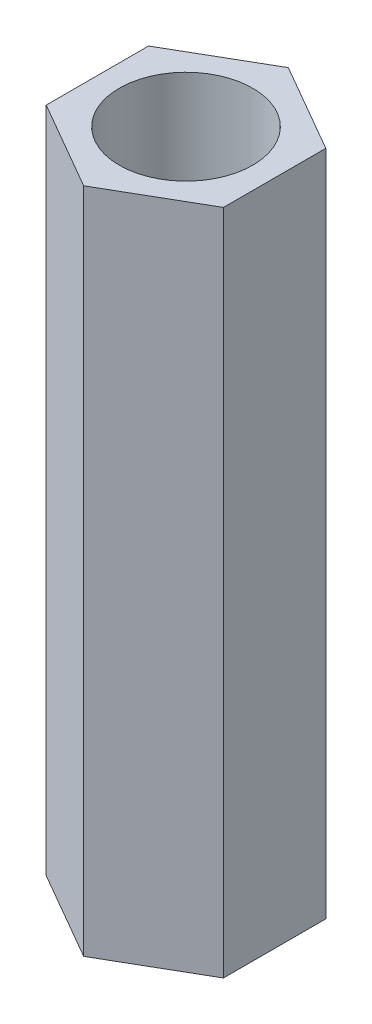
SolidWorks part; units mm, degrees
material "黄铜"
ref_plane "前视基准面" through (0, 0, 0) normal (0, 0, 1) x (1, 0, 0)
ref_plane "上视基准面" through (0, 0, 0) normal (0, 1, 0) x (1, 0, 0)
ref_plane "右视基准面" through (0, 0, 0) normal (1, 0, 0) x (0, 0, -1)
other "Configuration Table"
sketch "草图1" plane through (0, 0, 0) normal (0, 1, 0) x (1, 0, 0)
  line L0 (0, 0) -> (0, 3.1896) construction
  line L1 (1.9919, 1.15) -> (0, 2.3)
  line L2 (0, 2.3) -> (-1.9919, 1.15)
  line L3 (-1.9919, 1.15) -> (-1.9919, -1.15)
  line L4 (-1.9919, -1.15) -> (0, -2.3)
  line L5 (0, -2.3) -> (1.9919, -1.15)
  line L6 (1.9919, -1.15) -> (1.9919, 1.15)
  circle A0 centre (0, 0) radius 1.5
  circle A1 centre (0, 0) radius 1.9919 construction
  dimension "D1" = 3
  dimension "D2" = 4.6
extrude "凸台-拉伸1" add sketch "草图1" along normal blind 15
